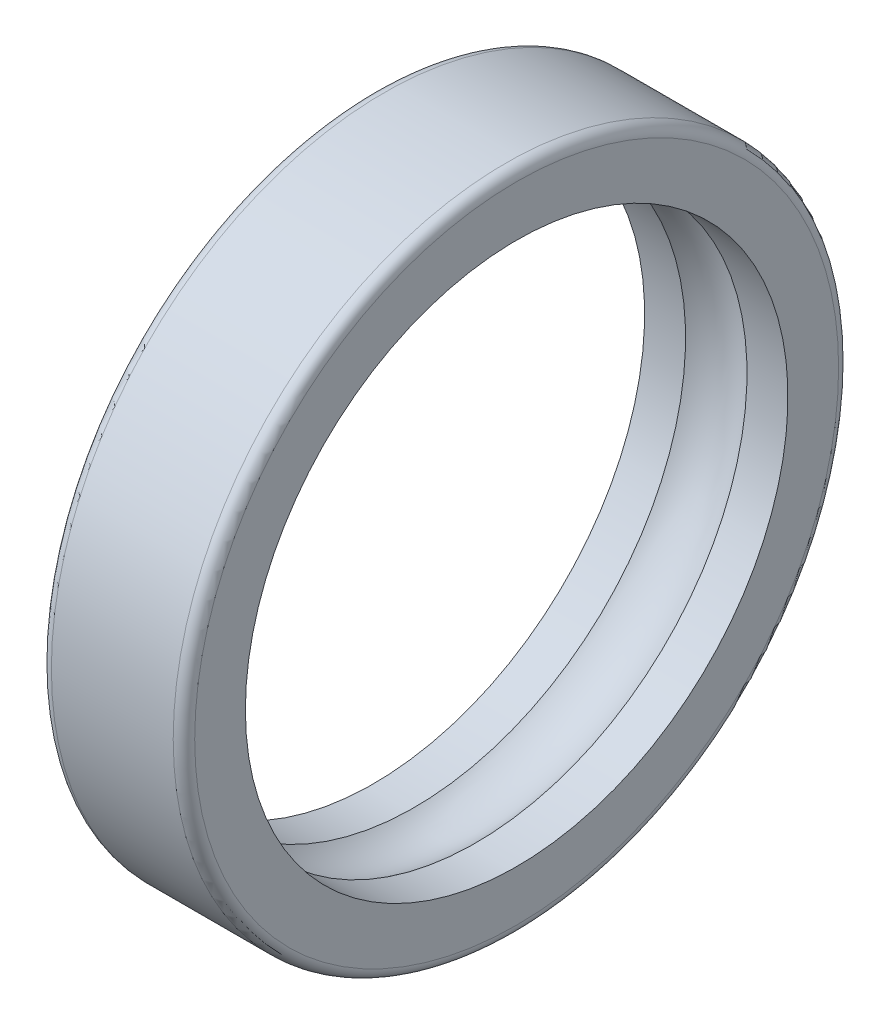
SolidWorks part; units mm, degrees
material "AISI 316 Stainless Steel Sheet (SS)"
ref_plane "Front Plane" through (0, 0, 0) normal (0, 0, 1) x (1, 0, 0)
ref_plane "Top Plane" through (0, 0, 0) normal (0, 1, 0) x (1, 0, 0)
ref_plane "Right Plane" through (0, 0, 0) normal (1, 0, 0) x (0, 0, -1)
sketch "Sketch1" plane through (0, 0, 0) normal (0, 0, 1) x (1, 0, 0)
  line L0 (-24.5928, 0) -> (22.9809, 0) construction
  line L1 (0, 0) -> (0, 53) construction
  line L2 (-14, 65) -> (14, 65)
  line L3 (-14, 65) -> (-14, 53)
  line L4 (-14, 53) -> (-6, 53)
  line L5 (14, 65) -> (14, 53)
  line L6 (-14, 65) -> (14, 53) construction
  line L7 (-14, 53) -> (14, 65) construction
  line L8 (6, 53) -> (14, 53)
  arc A0 (-6, 53) -> (6, 53) centre (0, 45) cw
  point P3 (0, 59)
  dimension "D5" = 10
  dimension "D1" = 28
  dimension "D2" = 53
  dimension "D3" = 65
  dimension "D4" = 8
revolve "Revolve1" add sketch "Sketch1" angle 360 about L0
fillet "Fillet1" radius 2.1 2 edges at (14, 0, 65) (-14, 0, 65)
